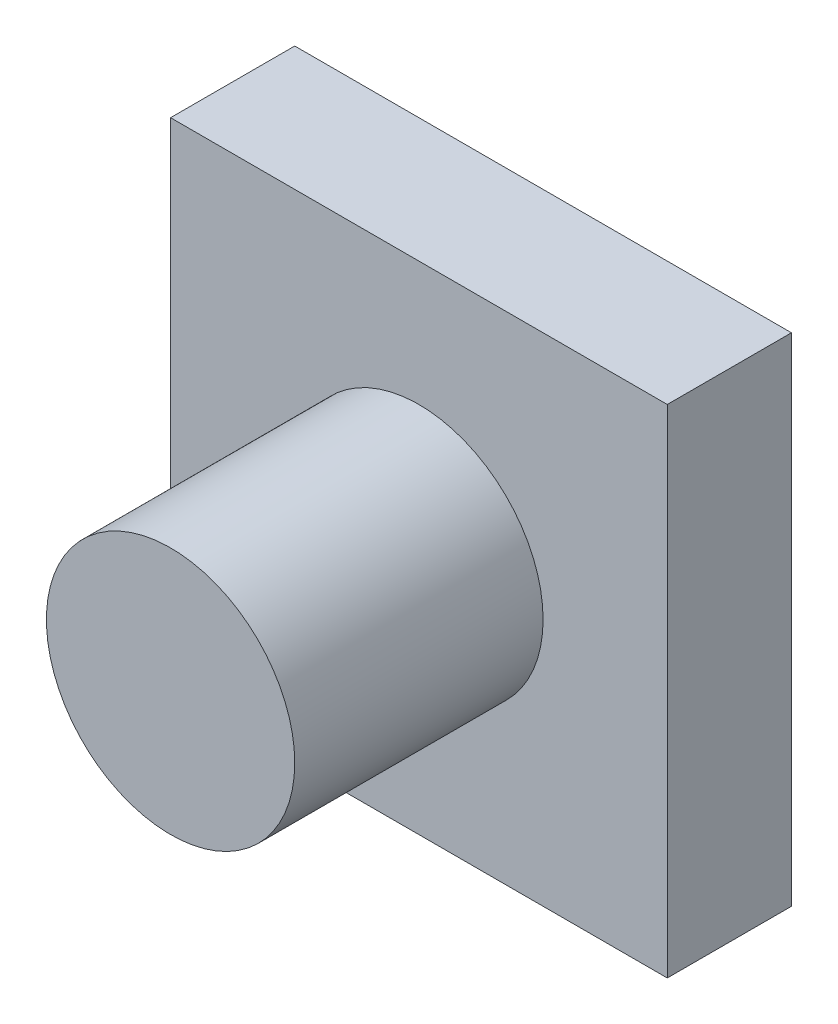
SolidWorks part; units mm, degrees
ref_plane "Front Plane" through (0, 0, 0) normal (0, 0, 1) x (1, 0, 0)
ref_plane "Top Plane" through (0, 0, 0) normal (0, 1, 0) x (1, 0, 0)
ref_plane "Right Plane" through (0, 0, 0) normal (1, 0, 0) x (0, 0, -1)
sketch "Sketch1" plane through (0, 0, 0) normal (0, 0, 1) x (1, 0, 0)
  line L1 (-20, -20) -> (20, -20)
  line L2 (-20, -20) -> (-20, 20)
  line L3 (-20, 20) -> (20, 20)
  line L4 (20, -20) -> (20, 20)
  point P0 (0, 0)
  dimension "D1" = 40
  dimension "D2" = 40
  dimension "D3" = 20
  dimension "D4" = 20
extrude "Boss-Extrude1" add sketch "Sketch1" along normal blind 10
sketch "Sketch2" plane through (0, 0, 10) normal (0, 0, 1) x (1, 0, 0)
  circle A0 centre (0, 0) radius 10
  dimension "D1" = 20
extrude "Boss-Extrude2" add sketch "Sketch2" along normal blind 20
